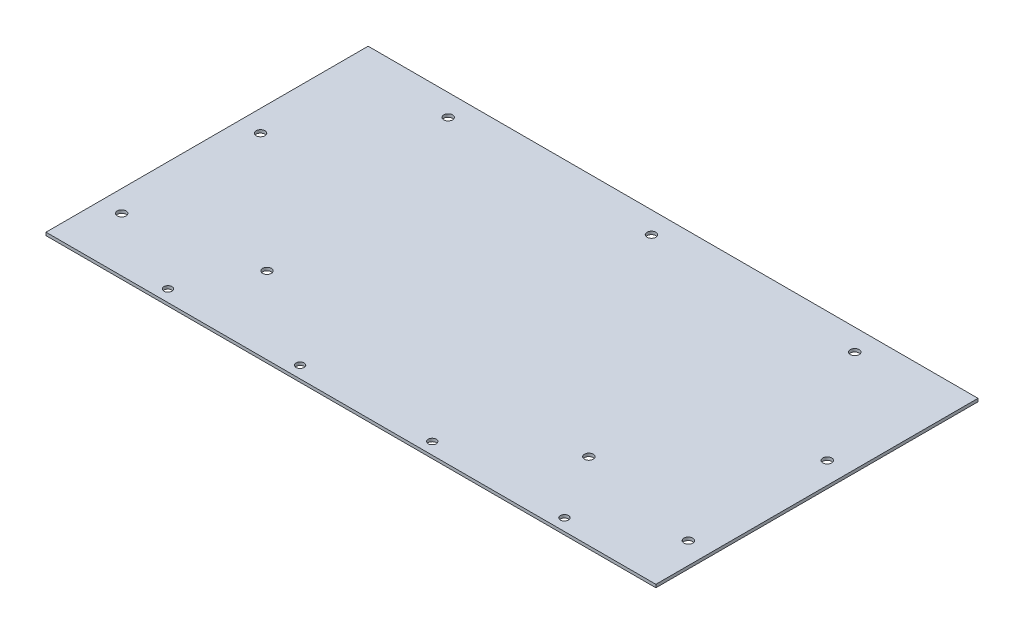
SolidWorks part; units mm, degrees
material "6061-T6 (SS)"
ref_plane "X-Y Datum" through (0, 0, 0) normal (0, 0, 1) x (1, 0, 0)
ref_plane "X-Z Datum" through (0, 0, 0) normal (0, 1, 0) x (1, 0, 0)
ref_plane "Y-Z Datum" through (0, 0, 0) normal (1, 0, 0) x (0, 0, -1)
sketch "Sketch1" plane through (0, 0, 0) normal (0, 0, 1) x (1, 0, 0)
  line L1 (-228.6, -1.143) -> (228.6, -1.143)
  line L2 (-228.6, -1.143) -> (-228.6, 1.143)
  line L3 (-228.6, 1.143) -> (228.6, 1.143)
  line L4 (228.6, -1.143) -> (228.6, 1.143)
  line L5 (-228.6, -1.143) -> (228.6, 1.143) construction
  line L6 (-228.6, 1.143) -> (228.6, -1.143) construction
  point P0 (0, 0)
  dimension "D1" = 2.286
  dimension "D2" = 457.2
extrude "Boss-Extrude1" add sketch "Sketch1" along normal blind 238.3152
sketch "Sketch2" plane through (0, 0, 0) normal (0, 0, -1) x (-1, 0, 0)
  line L22 (-228.6, 1.143) -> (-228.6, -1.143)
  line L23 (-228.6, -1.143) -> (228.6, -1.143)
  line L24 (228.6, -1.143) -> (228.6, 1.143)
  line L25 (228.6, 1.143) -> (-228.6, 1.143)
  line L26 (-228.6, 1.143) -> (-228.6, -1.143)
  line L27 (-228.6, -1.143) -> (228.6, -1.143)
  line L28 (228.6, -1.143) -> (228.6, 1.143)
  line L29 (228.6, 1.143) -> (-228.6, 1.143)
  dimension "D1" = 0
extrude "Boss-Extrude2" add sketch "Sketch2" along normal blind 3.175
sketch "Sketch9" plane through (0, 1.143, 0) normal (0, 1, 0) x (1, 0, 0)
  line L0 (-146.05, -238.3152) -> (-146.05, -229.4252) construction
  line L1 (228.6, -238.3152) -> (-228.6, -238.3152) construction
  line L2 (-228.6, -238.3152) -> (-228.6, 3.175) construction
  circle A0 centre (-146.05, -229.4252) radius 3
  dimension "D2" = 82.55
  dimension "D3" = 6
  dimension "D1" = 8.89
extrude "Cut-Extrude10" cut sketch "Sketch9" against normal blind 2.54
pattern_linear "LPattern1" count 4 spacing 99.06 along (1, 0, 0) of "Cut-Extrude10"
sketch "Sketch10" plane through (0, -1.143, 0) normal (0, -1, 0) x (1, 0, 0)
  circle A0 centre (151.13, 229.4252) radius 3 construction
  circle A1 centre (52.07, 229.4252) radius 3 construction
  circle A2 centre (-46.99, 229.4252) radius 3 construction
  circle A3 centre (-146.05, 229.4252) radius 3 construction
  circle A4 centre (151.13, 229.4252) radius 3
  circle A5 centre (52.07, 229.4252) radius 3
  circle A6 centre (-46.99, 229.4252) radius 3
  circle A7 centre (-146.05, 229.4252) radius 3
sketch "Sketch12" plane through (0, -1.143, 0) normal (0, -1, 0) x (1, 0, 0)
  point P0 (-212.419, 93.6448)
  point P1 (-152.4, 13.0175)
  point P3 (0, 13.0175)
  point P5 (152.4, 13.0175)
  point P7 (212.419, 93.6448)
  point P9 (212.419, 197.7848)
  point P11 (120.65, 180.586)
  point P15 (-120.65, 180.586)
  point P17 (-212.419, 197.7848)
hole_wizard "M6 Clearance Hole1" positions "Sketch12" profile "Sketch13" hole size "M6" standard "ANSI Metric" end condition through all
sketch "Sketch13" plane through (-212.419, -1.143, 93.6448) normal (1, 0, 0) x (0, 0, -1)
  line L0 (0, 0) -> (0, 2.286)
  line L1 (0, 2.286) -> (3.3, 2.286)
  line L2 (3.3, 2.286) -> (3.3, 0)
  line L5 (3.3, 0) -> (0, 0)
  line L11 (0, -6.35) -> (0, 107.95) construction
  dimension "Thru Hole Dia." = 6.6
  dimension "Thru Hole Depth" = 2.286
